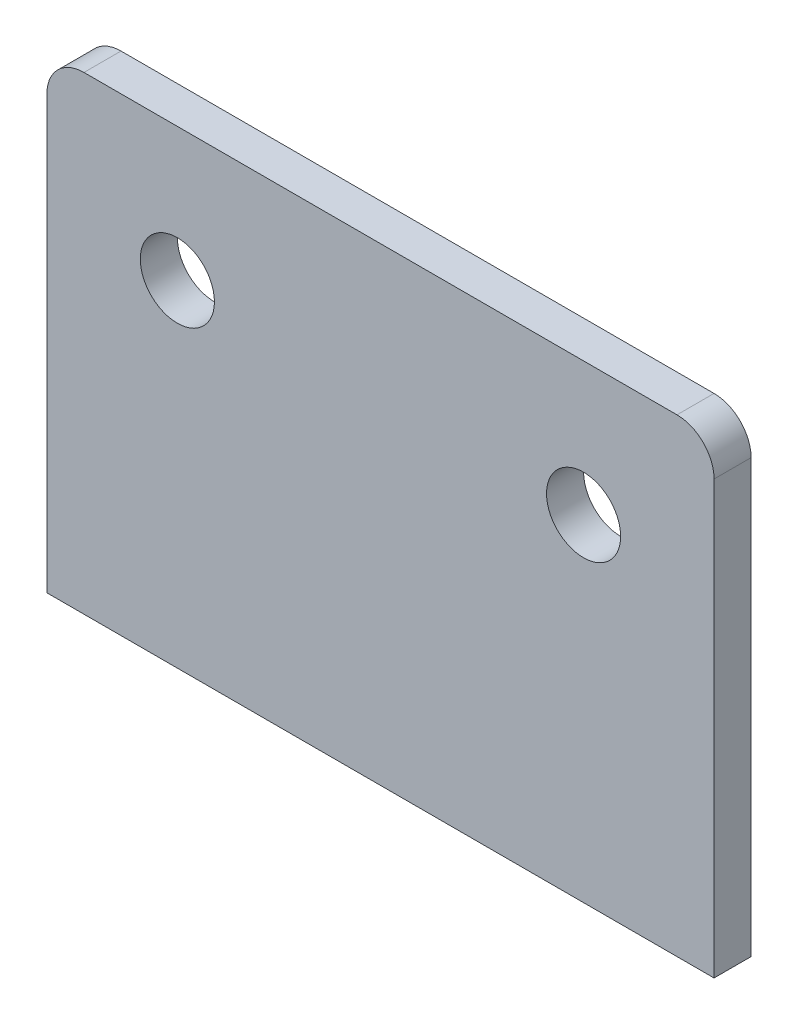
SolidWorks part; units mm, degrees
material "AISI 4130 Steel, annealed at 865C"
ref_plane "X-Y Datum" through (0, 0, 0) normal (0, 0, 1) x (1, 0, 0)
ref_plane "X-Z Datum" through (0, 0, 0) normal (0, 1, 0) x (1, 0, 0)
ref_plane "Y-Z Datum" through (0, 0, 0) normal (1, 0, 0) x (0, 0, -1)
sketch "Sketch1" plane through (0, 0, 0) normal (0, 0, 1) x (1, 0, 0)
  line L1 (-28.329, 3.0708) -> (-28.329, -34.9225)
  line L3 (28.821, -34.9225) -> (28.821, 3.0708)
  line L4 (-25.154, 6.2458) -> (25.646, 6.2458)
  line L5 (0, 0) -> (-28.329, 0) construction
  line L6 (-28.329, -34.9225) -> (-28.329, -57.1475)
  line L7 (28.821, -34.9225) -> (28.821, -57.1475)
  line L8 (-25.154, -60.3225) -> (25.646, -60.3225)
  line L9 (0, 0) -> (0, 6.2458) construction
  line L10 (0, 0) -> (0.246, -60.3225) construction
  arc A2 (25.646, 6.2458) -> (28.821, 3.0708) centre (25.646, 3.0708) cw
  arc A3 (-25.154, 6.2458) -> (-28.329, 3.0708) centre (-25.154, 3.0708) ccw
  arc A4 (28.821, -57.1475) -> (25.646, -60.3225) centre (25.646, -57.1475) cw
  arc A5 (-28.329, -57.1475) -> (-25.154, -60.3225) centre (-25.154, -57.1475) ccw
  point P4 (0, 0)
  point P10 (28.821, -60.3225)
  dimension "D1" = 25.4
  dimension "D4" = 3.175
  dimension "D2" = 57.15
  dimension "D3" = 37.9932
  dimension "D5" = 28.329
  dimension "D6" = 6.2458
  dimension "D7" = 60.3225
extrude "Boss-Extrude1" add sketch "Sketch1" against normal blind 3.175
sketch "Sketch2" plane through (0, 0, 0) normal (0, 0, 1) x (1, 0, 0)
  line L0 (0.246, -60.3225) -> (0.246, 6.2458) construction
  line L2 (-25.154, -60.3225) -> (25.646, -60.3225) construction
  line L3 (-17.153, -5.1842) -> (-17.153, 6.2458) construction
  line L4 (25.646, 6.2458) -> (-25.154, 6.2458) construction
  line L5 (-28.329, -5.1842) -> (-17.153, -5.1842) construction
  line L6 (-28.329, 3.0708) -> (-28.329, -57.1475) construction
  line L7 (-25.154, -60.3225) -> (25.646, -60.3225) construction
  circle A0 centre (-17.153, -5.1842) radius 3.175
  circle A1 centre (17.645, -5.1842) radius 3.175
  dimension "D1" = 11.176
  dimension "D3" = 6.35
  dimension "D2" = 11.43
extrude "Cut-Extrude1" cut sketch "Sketch2" against normal through all
sketch "Sketch3" plane through (0, 0, -3.175) normal (0, 0, -1) x (-1, 0, 0)
  line L0 (-28.821, -57.1475) -> (-28.821, 3.0708) construction
  line L1 (-28.821, -33.9467) -> (28.329, -33.9467)
  line L2 (-28.821, -33.9467) -> (-28.821, -63.1224)
  line L3 (-28.821, -63.1224) -> (28.329, -63.1224)
  line L4 (28.329, -33.9467) -> (28.329, -63.1224)
  line L5 (28.329, 3.0708) -> (28.329, -57.1475) construction
  point P6 (28.329, -33.9467)
extrude "Cut-Extrude2" cut sketch "Sketch3" against normal blind 5.08
